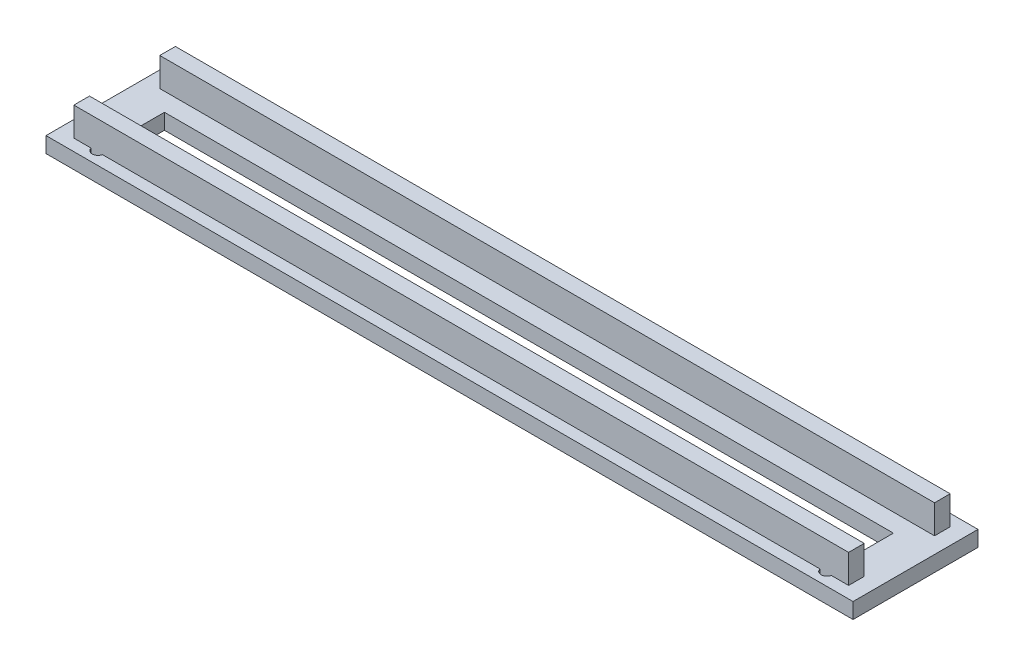
SolidWorks part; units mm, degrees
ref_plane "前视基准面" through (0, 0, 0) normal (0, 0, 1) x (1, 0, 0)
ref_plane "上视基准面" through (0, 0, 0) normal (0, 1, 0) x (1, 0, 0)
ref_plane "右视基准面" through (0, 0, 0) normal (1, 0, 0) x (0, 0, -1)
other "Configuration Table"
sketch "01_Rail_Base_Profile" plane through (0, 0, 0) normal (0, 1, 0) x (1, 0, 0)
  line L1 (-310, -48) -> (310, -48)
  line L2 (-310, -48) -> (-310, 48)
  line L3 (-310, 48) -> (310, 48)
  line L4 (310, -48) -> (310, 48)
  line L5 (-310, -48) -> (310, 48) construction
  line L6 (-310, 48) -> (310, -48) construction
  line L7 (-280, -13) -> (280, -13)
  line L8 (-280, -13) -> (-280, 13)
  line L9 (-280, 13) -> (280, 13)
  line L10 (280, -13) -> (280, 13)
  line L11 (-280, -13) -> (280, 13) construction
  line L12 (-280, 13) -> (280, -13) construction
  circle A0 centre (-280, -38) radius 4.5
  circle A1 centre (-280, 38) radius 4.5
  circle A2 centre (280, -38) radius 4.5
  circle A3 centre (280, 38) radius 4.5
  point P0 (0, 0)
  point P14 (0, 0)
extrude "01_Rail_Base" add sketch "01_Rail_Base_Profile" along normal blind 12
sketch "02_Guide_Rail_Profiles" plane through (0, 0, 0) normal (0, 1, 0) x (1, 0, 0)
  line L1 (-297.6, 27) -> (297.6, 27)
  line L2 (-297.6, 27) -> (-297.6, 39)
  line L3 (-297.6, 39) -> (297.6, 39)
  line L4 (297.6, 27) -> (297.6, 39)
  line L5 (-297.6, 27) -> (297.6, 39) construction
  line L6 (-297.6, 39) -> (297.6, 27) construction
  line L7 (-297.6, -39) -> (297.6, -39)
  line L8 (-297.6, -39) -> (-297.6, -27)
  line L9 (-297.6, -27) -> (297.6, -27)
  line L10 (297.6, -39) -> (297.6, -27)
  line L11 (-297.6, -39) -> (297.6, -27) construction
  line L12 (-297.6, -27) -> (297.6, -39) construction
  point P0 (0, 33)
  point P5 (0, -33)
extrude "02_Guide_Rails" add sketch "02_Guide_Rail_Profiles" along normal blind 34
